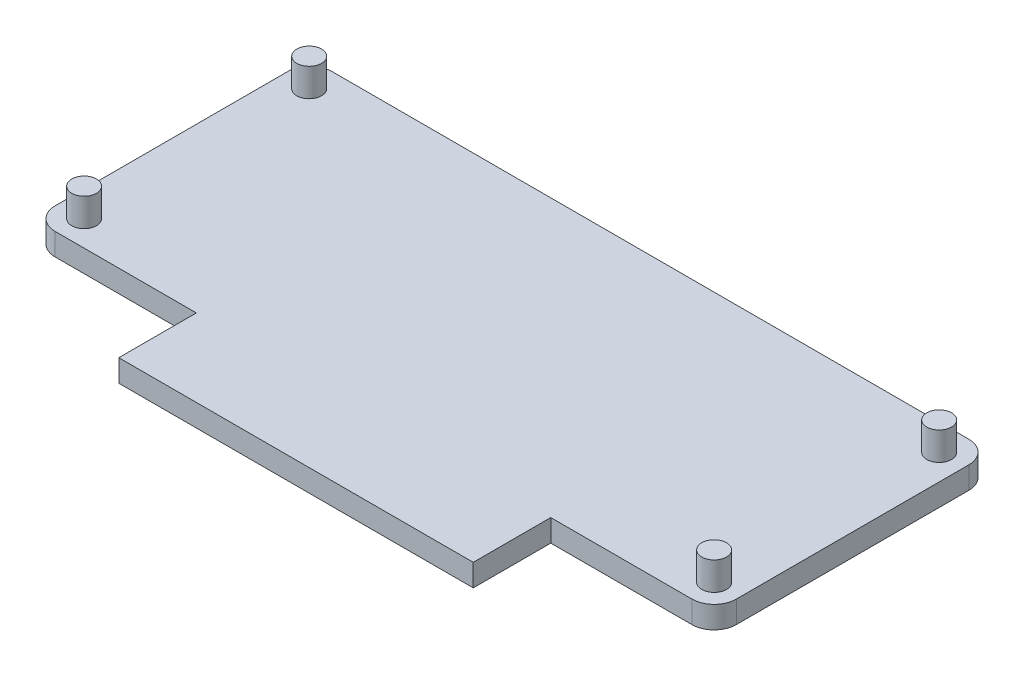
SolidWorks part; units mm, degrees
ref_plane "Front Plane" through (0, 0, 0) normal (0, 0, 1) x (1, 0, 0)
ref_plane "Top Plane" through (0, 0, 0) normal (0, 1, 0) x (1, 0, 0)
ref_plane "Right Plane" through (0, 0, 0) normal (1, 0, 0) x (0, 0, -1)
sketch "Sketch3" plane through (0, 0, 0) normal (0, 1, 0) x (1, 0, 0)
  line L0 (-16, 0) -> (16, 0)
  line L1 (-16, 0) -> (-16, 7)
  line L2 (16, 0) -> (16, 7)
  line L3 (16, 7) -> (30.75, 7)
  line L4 (-16, 7) -> (-30.75, 7)
  line L5 (-30.75, 7) -> (-30.75, 32)
  line L6 (30.75, 7) -> (30.75, 32)
  line L7 (-30.75, 32) -> (30.75, 32)
  point P8 (0, 0)
  point P10 (0, 0)
  dimension "D1" = 32
  dimension "D2" = 7
  dimension "D3" = 7
  dimension "D4" = 61.5
  dimension "D5" = 25
  dimension "D6" = 25
extrude "Boss-Extrude1" add sketch "Sketch3" along normal blind 2
sketch "Sketch4" plane through (0, 2, 0) normal (0, 1, 0) x (1, 0, 0)
  line L0 (-30.75, 7) -> (-16, 7) construction
  line L1 (-30.75, 32) -> (-30.75, 7) construction
  circle A0 centre (-28.44, 9.31) radius 1.1176
  circle A1 centre (-28.44, 29.63) radius 1.1176
  circle A2 centre (28.4408, 29.63) radius 1.1176
  circle A3 centre (28.4408, 9.31) radius 1.1176
  point P12 (28.4408, 9.31)
  point P13 (0, 0)
  point P14 (0, 0)
  point P15 (0, 0)
  point P16 (0, 0)
  point P17 (0, 0)
  point P18 (0, 0)
  dimension "D1" = 2.2352
  dimension "D2" = 2.2352
  dimension "D3" = 2.2352
  dimension "D4" = 2.2352
  dimension "D5" = 20.32
  dimension "D6" = 56.8808
  dimension "D7" = 2.31
  dimension "D8" = 2.31
extrude "Boss-Extrude2" add sketch "Sketch4" along normal blind 2.54
fillet "Fillet1" radius 2 4 edges at (30.75, 1, -7) (30.75, 1, -32) (-30.75, 1, -32) (-30.75, 1, -7)
